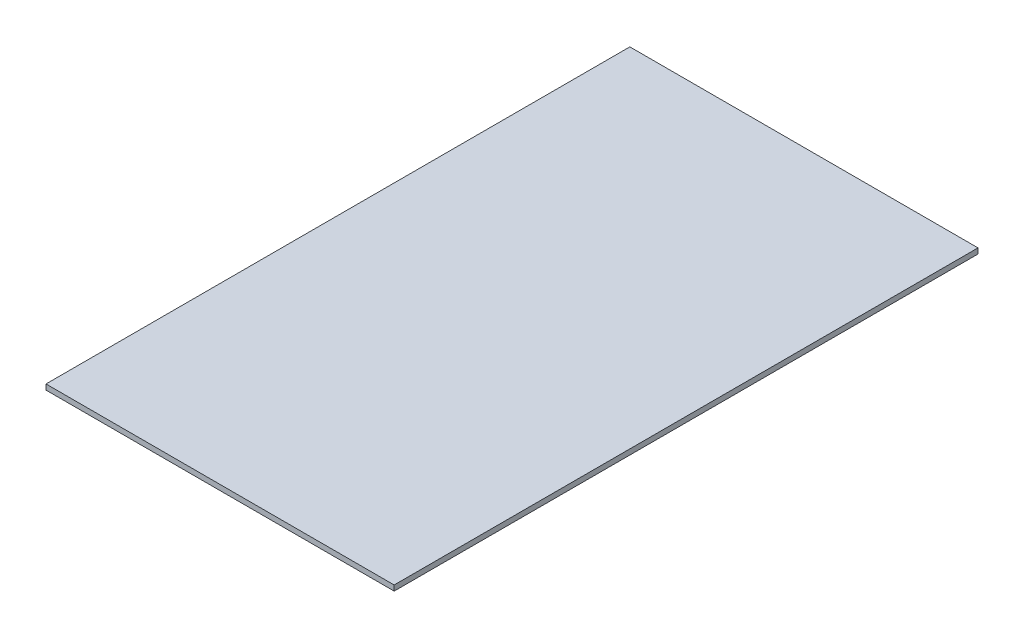
SolidWorks part; units mm, degrees
ref_plane "Front Plane" through (0, 0, 0) normal (0, 0, 1) x (1, 0, 0)
ref_plane "Top Plane" through (0, 0, 0) normal (0, 1, 0) x (1, 0, 0)
ref_plane "Right Plane" through (0, 0, 0) normal (1, 0, 0) x (0, 0, -1)
sketch "Sketch1" plane through (0, 0, 0) normal (0, 1, 0) x (1, 0, 0)
  line L1 (-65, 109) -> (65, 109)
  line L2 (-65, 109) -> (-65, -109)
  line L3 (-65, -109) -> (65, -109)
  line L4 (65, 109) -> (65, -109)
  line L5 (-65, 109) -> (65, -109) construction
  line L6 (-65, -109) -> (65, 109) construction
  point P0 (0, 0)
  dimension "D1" = 130
  dimension "D2" = 218
extrude "Boss-Extrude1" add sketch "Sketch1" along normal mid plane 2
